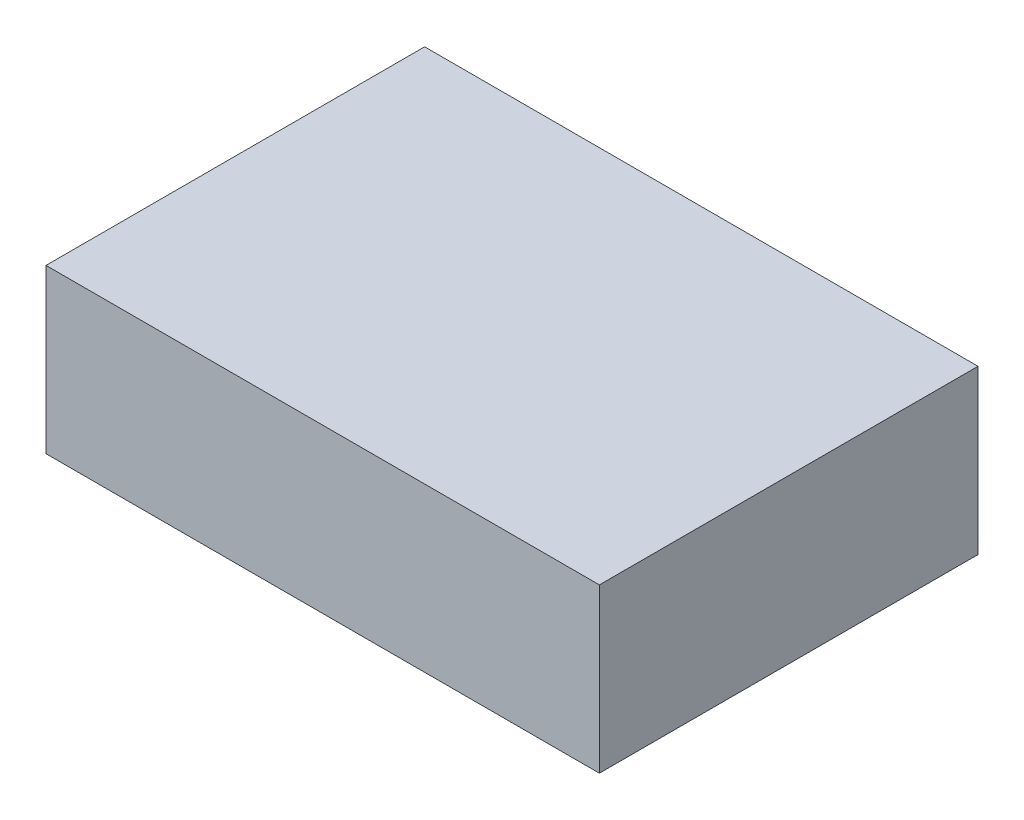
SolidWorks part; units mm, degrees
ref_plane "Front Plane" through (0, 0, 0) normal (0, 0, 1) x (1, 0, 0)
ref_plane "Top Plane" through (0, 0, 0) normal (0, 1, 0) x (1, 0, 0)
ref_plane "Right Plane" through (0, 0, 0) normal (1, 0, 0) x (0, 0, -1)
sketch "Sketch1" plane through (0, 0, 0) normal (0, 1, 0) x (1, 0, 0)
  line L1 (0, 0) -> (60.325, 0)
  line L2 (0, 0) -> (0, 41.275)
  line L3 (0, 41.275) -> (60.325, 41.275)
  line L4 (60.325, 0) -> (60.325, 41.275)
  dimension "D1" = 60.325
  dimension "D2" = 41.275
extrude "Boss-Extrude1" add sketch "Sketch1" along normal blind 17.78
